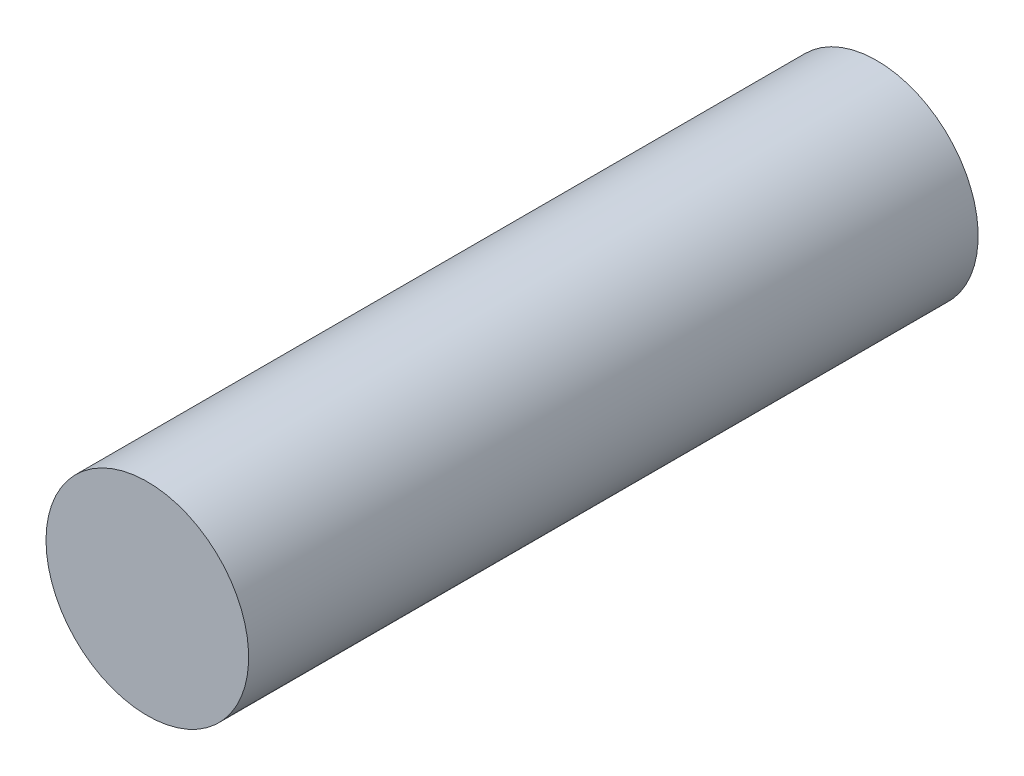
SolidWorks part; units mm, degrees
ref_plane "Front Plane" through (0, 0, 0) normal (0, 0, 1) x (1, 0, 0)
ref_plane "Top Plane" through (0, 0, 0) normal (0, 1, 0) x (1, 0, 0)
ref_plane "Right Plane" through (0, 0, 0) normal (1, 0, 0) x (0, 0, -1)
sketch "Sketch1" plane through (0, 0, 0) normal (0, 0, 1) x (1, 0, 0)
  circle A0 centre (0, 0) radius 12.5
extrude "Boss-Extrude1" add sketch "Sketch1" along normal blind 90
